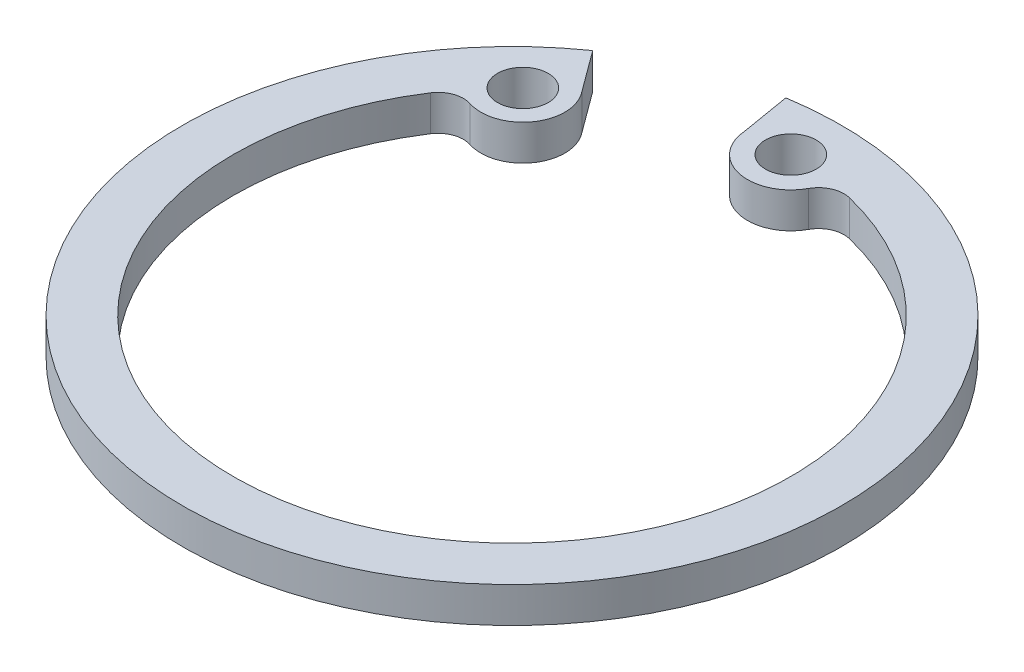
SolidWorks part; units mm, degrees
ref_plane "前视基准面" through (0, 0, 0) normal (0, 0, 1) x (1, 0, 0)
ref_plane "上视基准面" through (0, 0, 0) normal (0, 1, 0) x (1, 0, 0)
ref_plane "右视基准面" through (0, 0, 0) normal (1, 0, 0) x (0, 0, -1)
sketch "草图1" plane through (0, 0, 0) normal (0, 1, 0) x (1, 0, 0)
  line L0 (-1.7047, 10.8671) -> (-2.0368, 12.8394)
  line L1 (-6.2753, 9.0344) -> (-7.4611, 10.6458)
  arc A0 (-7.4611, 10.6458) -> (-2.0368, 12.8394) centre (0, 0) ccw
  circle A1 centre (0, 11) radius 1
  arc A2 (-1.7047, 10.8671) -> (1.5043, 10.1871) centre (0, 11) ccw
  arc A3 (-8.0701, 6.4125) -> (-6.2753, 9.0344) centre (-7.5611, 7.9893) ccw
  arc A4 (-9.215, 6.007) -> (2.6224, 10.6828) centre (0, 0) ccw
  circle A5 centre (-7.5611, 7.9893) radius 1
  arc A6 (2.6224, 10.6828) -> (1.5043, 10.1871) centre (2.384, 9.7117) ccw
  arc A7 (-8.0701, 6.4125) -> (-9.215, 6.007) centre (-8.3773, 5.4609) ccw
  dimension "D1" = 26
  dimension "D2" = 2
  dimension "D3" = 2
  dimension "D4" = 1
extrude "拉伸1" add sketch "草图1" along normal blind 1.4
